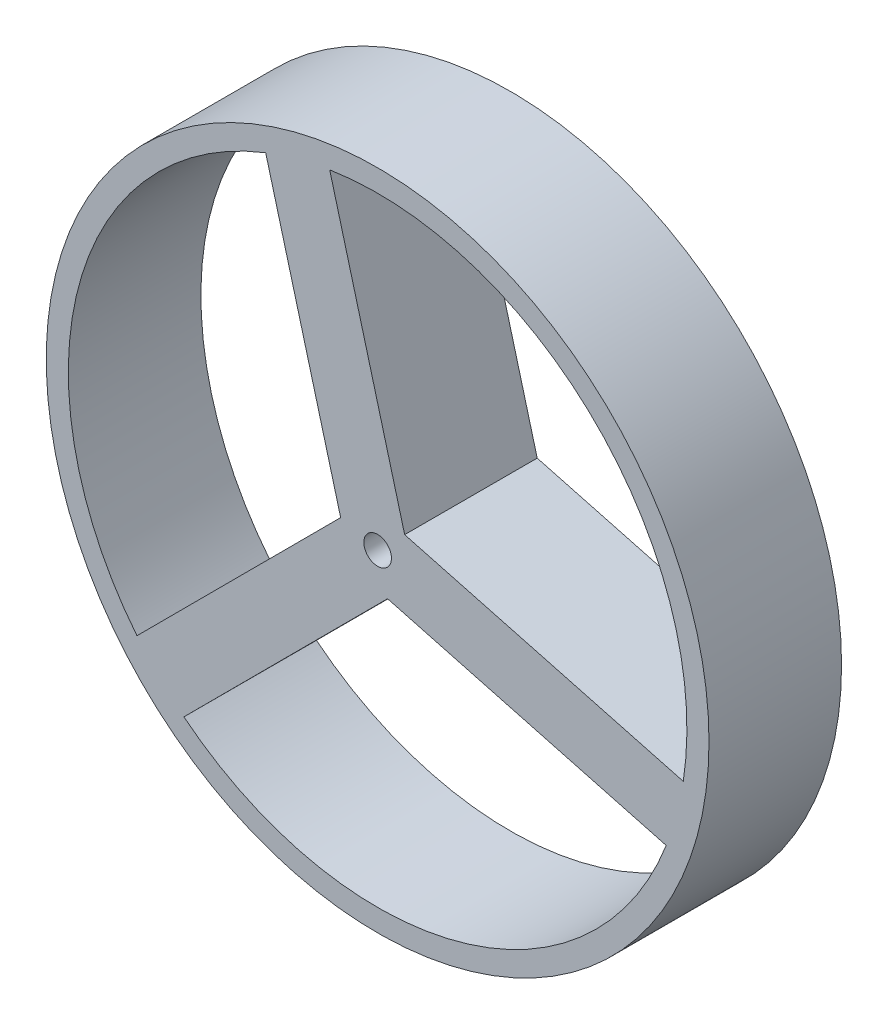
SolidWorks part; units mm, degrees
ref_plane "Front Plane" through (0, 0, 0) normal (0, 0, 1) x (1, 0, 0)
ref_plane "Top Plane" through (0, 0, 0) normal (0, 1, 0) x (1, 0, 0)
ref_plane "Right Plane" through (0, 0, 0) normal (1, 0, 0) x (0, 0, -1)
sketch "Sketch2" plane through (0, 0, 0) normal (0, 0, 1) x (1, 0, 0)
  line L1 (-8.4469, 31.383) -> (0, 0) construction
  line L2 (0, 0) -> (27.0541, -7.2165) construction
  line L3 (0, 0) -> (-19.7767, -19.8212) construction
  line L4 (-10.1324, 26.1024) -> (-3.3471, 0.8928)
  line L5 (-3.3471, 0.8928) -> (-21.7866, -17.5882)
  line L6 (-17.5392, -21.8261) -> (0.9003, -3.3451)
  line L7 (0.9003, -3.3451) -> (26.1251, -10.0736)
  line L8 (-4.3386, 27.6618) -> (2.4467, 2.4522)
  line L9 (2.4467, 2.4522) -> (27.6715, -4.2763)
  line L10 (0, 0) -> (0.9003, -3.3451) construction
  line L11 (-3.3471, 0.8928) -> (0, 0) construction
  line L12 (0, 0) -> (2.4467, 2.4522) construction
  circle A0 centre (0, 0) radius 30
  arc A1 (-10.1324, 26.1024) -> (-21.7866, -17.5882) centre (0, 0) ccw
  arc A3 (27.6715, -4.2763) -> (-4.3386, 27.6618) centre (0, 0) ccw
  arc A4 (-17.5392, -21.8261) -> (26.1251, -10.0736) centre (0, 0) ccw
  dimension "D1" = 60
  dimension "D2" = 56
  dimension "D3" = 120
  dimension "D4" = 120
  dimension "D5" = 3
  dimension "D6" = 3
  dimension "D7" = 3
  dimension "D8" = 3
  dimension "D9" = 3
  dimension "D10" = 3
extrude "Boss-Extrude1" add sketch "Sketch2" along normal blind 12
sketch "Sketch3" plane through (0, 0, 12) normal (0, 0, 1) x (1, 0, 0)
  circle A0 centre (0, 0) radius 6
  circle A1 centre (0, 0) radius 3
  dimension "D1" = 6
  dimension "D2" = 12
sketch "Sketch4" plane through (0, 0, 12) normal (0, 0, 1) x (1, 0, 0)
  circle A0 centre (0, 0) radius 1.25
  dimension "D1" = 2.5
extrude "Cut-Extrude1" cut sketch "Sketch4" against normal through all
